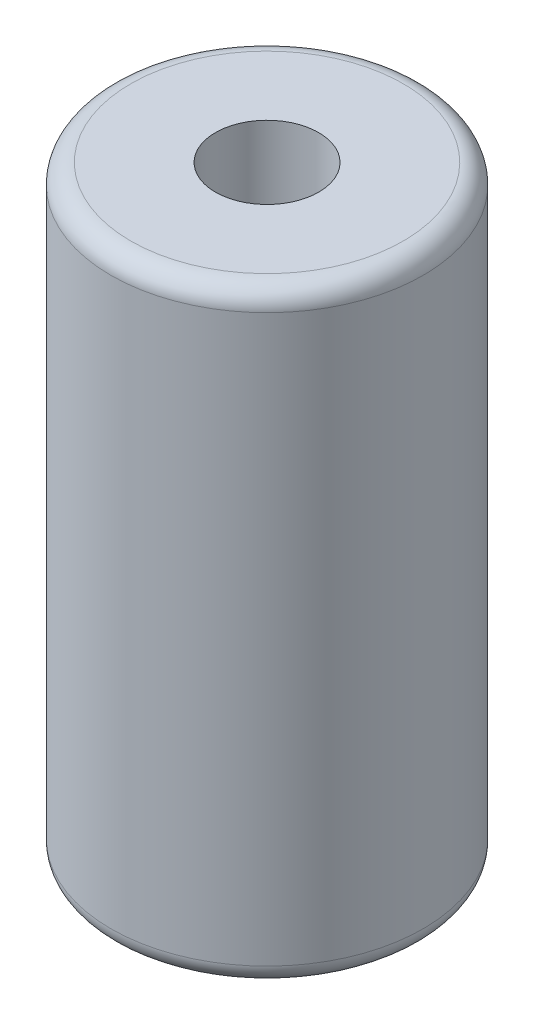
SolidWorks part; units mm, degrees
ref_plane "Front" through (0, 0, 0) normal (0, 0, 1) x (1, 0, 0)
ref_plane "Top" through (0, 0, 0) normal (0, 1, 0) x (1, 0, 0)
ref_plane "Right" through (0, 0, 0) normal (1, 0, 0) x (0, 0, -1)
sketch "Sketch1" plane through (0, 0, 0) normal (0, 1, 0) x (1, 0, 0)
  circle A0 centre (0, 0) radius 1.05
  circle A1 centre (0, 0) radius 3.175
  dimension "D1" = 2.1
  dimension "D2" = 6.35
extrude "Boss-Extrude1" add sketch "Sketch1" along normal blind 12.317
fillet "Fillet1" radius 0.4032 2 edges at (0, 0, 3.175) (0, 12.317, 3.175)
ref_plane "Plane1" through (0, 6.1585, 0) normal (0, 1, 0) x (1, 0, 0)
